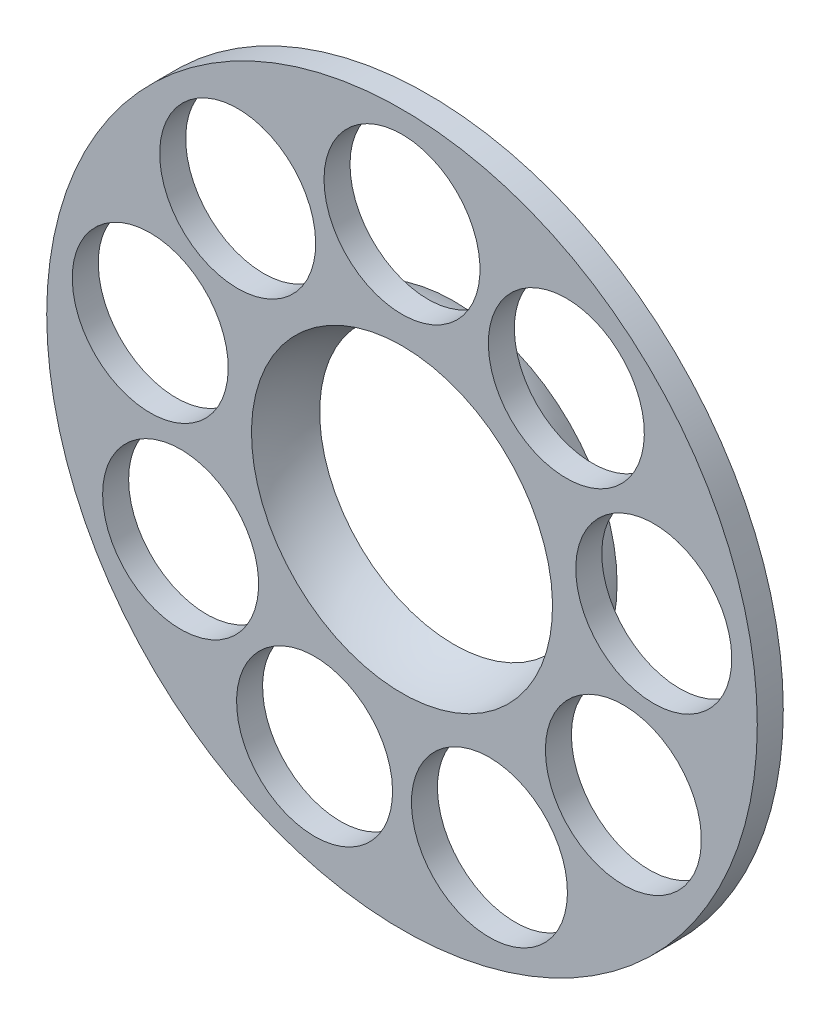
SolidWorks part; units mm, degrees
ref_plane "前视基准面" through (0, 0, 0) normal (0, 0, 1) x (1, 0, 0)
ref_plane "上视基准面" through (0, 0, 0) normal (0, 1, 0) x (1, 0, 0)
ref_plane "右视基准面" through (0, 0, 0) normal (1, 0, 0) x (0, 0, -1)
sketch "草图4" plane through (0, 0, 0) normal (1, 0, 0) x (0, 0, -1)
  line L0 (0, 0) -> (6, 0) construction
  line L1 (55, 0) -> (-55, 0) construction
  line L2 (0, 17.3706) -> (0, 41)
  line L3 (0, 55) -> (0, -55) construction
  line L4 (0, 41) -> (3, 41)
  line L5 (3, 41) -> (3, 19.8493)
  line L7 (6, 18.8215) -> (6, 15.5)
  arc A0 (0, 17.3706) -> (6, 15.5) centre (-2.124, 0) cw
  arc A1 (3, 19.8493) -> (6, 18.8215) centre (-2.124, 0) cw
  point P13 (20.4777, 18.9585)
  point P14 (4.1133, 25.1738)
  point P15 (17.8148, 19.3874)
  point P16 (0, 22.4202)
  point P17 (6.0056, 4.7643)
  point P19 (-1.1216, 0)
  point P20 (-2.124, 0)
  point P21 (6.3494, 25.157)
  dimension "D2" = 17.5
  dimension "D3" = 3
  dimension "D1" = 6
  dimension "D4" = 82
  dimension "D5" = 31
  dimension "D6" = 3
  dimension "D7" = 6
revolve "旋转1" add sketch "草图4" angle 360 about L0
sketch "草图5" plane through (0, 0, -3) normal (0, 0, -1) x (-1, 0, 0)
  line L0 (0, 3.3) -> (0, -3.3) construction
  circle A0 centre (0, 29.5) radius 9
  dimension "D1" = 18
  dimension "D2" = 29.5
extrude "切除-拉伸1" cut sketch "草图5" against normal through all
pattern_circular "阵列(圆周)1" count 9 over 360 about axis through (0, 0, 0) along (0, 0, 1) of "切除-拉伸1"
